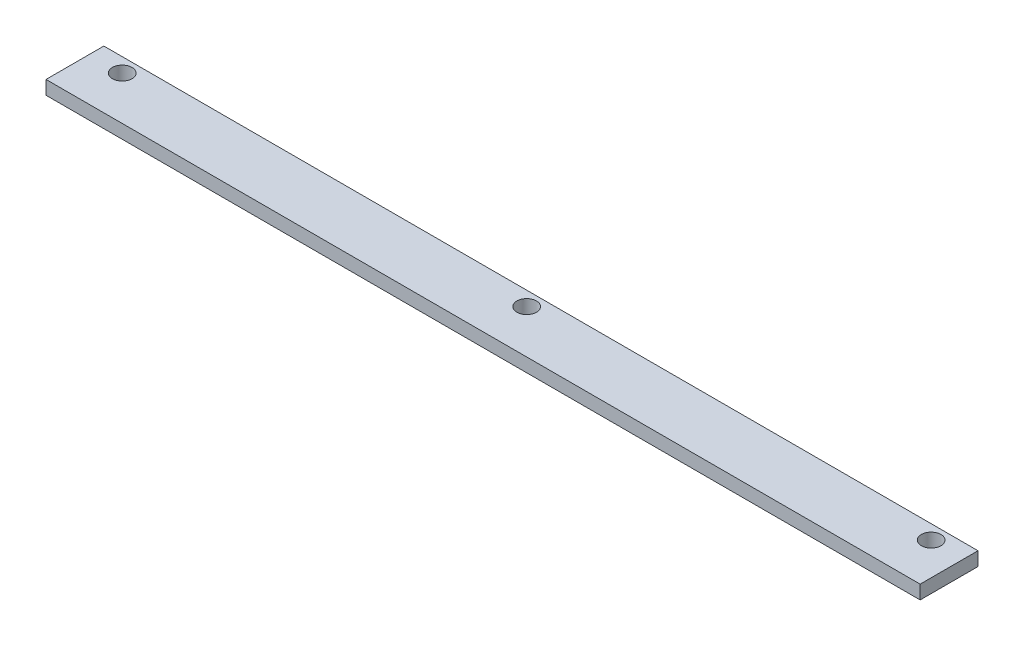
SolidWorks part; units mm, degrees
ref_plane "Front Plane" through (0, 0, 0) normal (1, 0, 0) x (0, 1, 0)
ref_plane "Top Plane" through (0, 0, 0) normal (0, 0, 1) x (0, 1, 0)
ref_plane "Right Plane" through (0, 0, 0) normal (0, 1, 0) x (-1, 0, 0)
sketch "Sketch1" plane through (0, 0, 0) normal (0, 0, 1) x (0, 1, 0)
  line L0 (2.9, 0.1) -> (2.9, 178.4)
  line L1 (0, 0) -> (3, 0)
  line L2 (0, 0) -> (0, 178.5)
  line L3 (0, 178.5) -> (3, 178.5)
  line L4 (3, 0) -> (3, 178.5)
  line L5 (0.1, 178.4) -> (2.9, 178.4)
  line L6 (0.1, 0.1) -> (0.1, 178.4)
  line L7 (0.1, 0.1) -> (2.9, 0.1)
  dimension "D1" = 178.5
  dimension "D2" = 3
  dimension "D3" = 0.1
extrude "Boss-Extrude1" add sketch "Sketch1" along normal blind 11.8 contours L0 L5 L6 L7
sketch "Sketch2" plane through (0, 2.9, 0) normal (0, 1, 0) x (-1, 0, 0)
  line L1 (178.4, 0) -> (171.75, 0)
  line L2 (178.4, 0) -> (178.4, 2.9)
  line L3 (178.4, 2.9) -> (171.75, 2.9)
  line L4 (171.75, 0) -> (171.75, 2.9)
  circle A0 centre (171.75, 2.9) radius 2
  dimension "D1" = 6.65
  dimension "D2" = 2.9
extrude "Cut-Extrude1" cut sketch "Sketch2" against normal up to next contours A0
pattern_linear "LPattern1" count 3 spacing 82.5 along (1, 0, 0) of "Cut-Extrude1"
ref_plane "Plane1" through (0, 0, 5.9) normal (0, 0, -1) x (-1, 0, 0)
mirror "Mirror1" [suppressed] about plane through (0, 0, 5.9) normal (0, 0, -1)
equation "\"whitekey_cutout_length\"= 101.5"
equation "\"mount_recess_length\"=50"
equation "\"mount_recess_height\"=12.5"
equation "\"mount_recess_depth\"=1.5"
equation "\"wall_thickness\"=8"
equation "\"base_mount_height\"=35"
equation "\"base_rear_length\"=80"
equation "\"D1@Sketch1\"=\"base_rear_length\"-\"wall_thickness\"+111.5-5"
equation "\"D2@Sketch1\"=\"wall_thickness\"-5"
